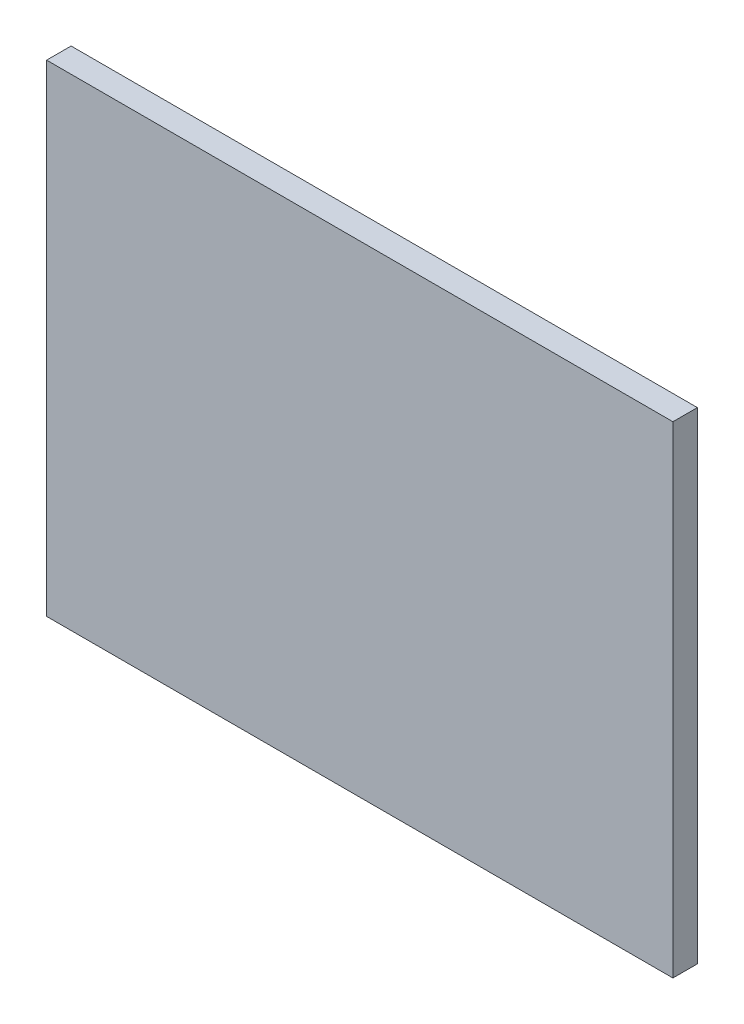
SolidWorks part; units mm, degrees
ref_plane "Front Plane" through (0, 0, 0) normal (0, 0, 1) x (1, 0, 0)
ref_plane "Top Plane" through (0, 0, 0) normal (0, 1, 0) x (1, 0, 0)
ref_plane "Right Plane" through (0, 0, 0) normal (1, 0, 0) x (0, 0, -1)
sketch "Sketch1" plane through (0, 0, 0) normal (0, 0, 1) x (1, 0, 0)
  line L1 (32.5, -25) -> (-32.5, -25)
  line L2 (32.5, -25) -> (32.5, 25)
  line L3 (32.5, 25) -> (-32.5, 25)
  line L4 (-32.5, -25) -> (-32.5, 25)
  line L5 (32.5, -25) -> (-32.5, 25) construction
  line L6 (32.5, 25) -> (-32.5, -25) construction
  point P0 (0, 0)
  dimension "D1" = 50
  dimension "D2" = 65
extrude "Boss-Extrude1" add sketch "Sketch1" along normal blind 2.54
sketch "Sketch2" plane through (0, 0, 2.54) normal (0, 0, 1) x (1, 0, 0)
  line L0 (-12.0406, -22.1111) -> (-8.0999, -14.8646)
  line L1 (-8.0999, -14.8646) -> (-11.0508, -13.6133)
  line L2 (-11.0508, -13.6133) -> (-15.6265, -19.7205)
  line L3 (-15.6265, -19.7205) -> (-12.0406, -22.1111)
  line L4 (-11.8675, -16.6471) -> (-10.4045, -17.5548)
  line L5 (-10.4045, -17.5548) -> (-9.1551, -15.3229)
  line L6 (-9.1551, -15.3229) -> (-10.6608, -15.1093)
  line L7 (-10.6608, -15.1093) -> (-11.8675, -16.6471)
  line L8 (-12.6879, -17.8424) -> (-13.7914, -19.121)
  line L9 (-13.7914, -18.1576) -> (-12.5653, -18.9809)
  line L10 (-16.1474, 2.0689) -> (-16.5784, 2.8101)
  line L11 (-16.5784, 2.8101) -> (-15.9751, 4.1202)
  line L12 (-15.9751, 4.1202) -> (-15.0615, 4.3098)
  line L13 (-15.0615, 4.3098) -> (-14.2331, 3.3179)
  line L14 (-14.2331, 3.3179) -> (-16.1474, 2.0689)
  line L15 (-14.2331, 3.3179) -> (-13.3481, 2.2583)
  line L16 (-13.3481, 2.2583) -> (-14.0719, 0.6866)
  line L17 (-14.0719, 0.6866) -> (-13.0102, 0.483)
  line L18 (-13.0102, 0.483) -> (-11.5568, 0.7846)
  line L19 (-11.5568, 0.7846) -> (-11.0508, 2.4395)
  line L20 (-11.0508, 2.4395) -> (-11.6794, 2.6317)
  line L21 (-11.6794, 2.6317) -> (-13.3481, 2.2583)
  line L22 (-11.6794, 2.6317) -> (-11.6794, 4.3098)
  line L23 (-11.6794, 4.3098) -> (-12.8281, 4.4649)
  line L24 (-12.8281, 4.4649) -> (-14.2331, 3.3179)
  line L25 (-12.8281, 4.4649) -> (-13.3481, 5.482)
  line L26 (-13.3481, 5.482) -> (-14.2331, 5.3268)
  line L27 (-14.2331, 5.3268) -> (-14.8029, 4.9821)
  line L28 (-14.8029, 4.9821) -> (-15.0615, 4.3098)
  line L29 (-11.5568, 0.7846) -> (-8.6275, 2.0689)
  line L30 (-8.6275, 2.0689) -> (-5.8634, 1.7504)
  line L31 (-14.0719, 0.6866) -> (-14.8774, 0.7794)
  line L32 (-17.9792, 2.713) -> (-18.9998, 4.1202)
  line L33 (-18.9998, 4.1202) -> (-19.9976, 3.7421)
  line L34 (-19.9976, 3.7421) -> (-20.847, 2.8481)
  line L35 (-20.847, 2.8481) -> (-21.1712, 3.2951)
  line L36 (-21.1712, 3.2951) -> (-21.0091, 4.7032)
  line L37 (-21.0091, 4.7032) -> (-19.5424, 6.2468)
  line L38 (-19.5424, 6.2468) -> (-18.4895, 5.475)
  line L39 (-18.4895, 5.475) -> (-18.9998, 4.1202)
  line L40 (-18.4895, 5.475) -> (-17.1317, 5.475)
  line L41 (-17.1317, 5.475) -> (-15.9751, 4.1202)
  line L42 (-17.1317, 5.475) -> (-17.1317, 6.2468)
  line L43 (-17.1317, 6.2468) -> (-15.0615, 6.834)
  line L44 (-15.0615, 6.834) -> (-14.4556, 5.8609)
  line L45 (-14.4556, 5.8609) -> (-14.0719, 5.3551)
  line L46 (-11.0508, 2.4395) -> (-9.8042, 3.3179)
  line L47 (-9.8042, 3.3179) -> (-8.4112, 2.8787)
  line L48 (-8.4112, 2.8787) -> (-8.6275, 2.0689)
  line L49 (-9.8042, 3.3179) -> (-9.8042, 4.1202)
  line L50 (-9.8042, 4.1202) -> (-11.6794, 4.9821)
  line L51 (-11.6794, 4.9821) -> (-11.9703, 4.3491)
  line L52 (-11.6794, 4.9821) -> (-11.8675, 5.567)
  line L53 (-11.8675, 5.567) -> (-11.6023, 6.4083)
  line L54 (-11.6023, 6.4083) -> (-10.857, 7.635)
  line L55 (-10.857, 7.635) -> (-9.7221, 7.1684)
  line L56 (-9.7221, 7.1684) -> (-9.1551, 5.567)
  line L57 (-9.1551, 5.567) -> (-10.2168, 4.3098)
  line L58 (-13.5123, 5.4532) -> (-13.3481, 6.4083)
  line L59 (-13.3481, 6.4083) -> (-12.5653, 6.834)
  line L60 (-12.5653, 6.834) -> (-11.6023, 6.4083)
  line L61 (-15.0615, 6.834) -> (-15.0615, 7.2987)
  line L62 (-15.0615, 7.2987) -> (-14.4556, 7.7382)
  line L63 (-14.4556, 7.7382) -> (-13.7356, 7.9424)
  line L64 (-13.7356, 7.9424) -> (-12.8281, 6.6911)
  line L65 (-16.9544, 6.297) -> (-17.1317, 6.922)
  line L66 (-17.1317, 6.922) -> (-17.1317, 8.1816)
  line L67 (-17.1317, 8.1816) -> (-16.5784, 8.5513)
  line L68 (-16.5784, 8.5513) -> (-15.8076, 8.2313)
  line L69 (-15.8076, 8.2313) -> (-15.3466, 8.0399)
  line L70 (-15.3466, 8.0399) -> (-15.0615, 7.2987)
  line L71 (-19.016, 5.8609) -> (-18.4895, 7.2987)
  line L72 (-18.4895, 7.2987) -> (-17.1317, 8.1816)
  line L73 (-18.4895, 7.2987) -> (-19.016, 7.4915)
  line L74 (-19.016, 7.4915) -> (-20.2516, 7.635)
  line L75 (-21.0091, 4.7032) -> (-22.5161, 5.4117)
  line L76 (-17.1317, 8.1816) -> (-17.505, 9.4976)
  line L77 (-16.5784, 8.5513) -> (-15.8076, 8.5513)
  line L78 (-15.8076, 8.5513) -> (-16.4497, 10.1095)
  line L79 (-15.8076, 8.5513) -> (-14.4556, 9.009)
  line L80 (-14.4556, 9.009) -> (-13.7356, 7.9424)
  line L81 (-14.4556, 9.009) -> (-15.3466, 10.6357)
  line L82 (-14.4556, 9.009) -> (-13.7356, 9.2013)
  line L83 (-13.7356, 9.2013) -> (-12.5653, 9.009)
  line L84 (-12.5653, 9.009) -> (-11.9703, 8.5513)
  line L85 (-11.9703, 8.5513) -> (-11.6023, 8.6496)
  line L86 (-11.6023, 8.6496) -> (-10.6608, 9.4976)
  line L87 (-10.6608, 9.4976) -> (-10.2168, 9.156)
  line L88 (-10.2168, 9.156) -> (-9.5945, 10.726)
  line L89 (-12.5653, 6.834) -> (-12.0981, 8.6496)
  line L90 (-11.6023, 8.6496) -> (-11.395, 8.0399)
  line L91 (-11.395, 8.0399) -> (-10.857, 7.635)
  line L92 (-9.7221, 7.1684) -> (-9.4383, 7.6356)
  line L93 (-9.4383, 7.6356) -> (-9.7221, 8.8809)
  line L94 (-9.7221, 8.8809) -> (-10.2168, 9.156)
  line L95 (-9.4383, 7.6356) -> (-9.0078, 7.4915)
  line L96 (-9.0078, 7.4915) -> (-8.4112, 7.5635)
  line L97 (-8.4112, 7.5635) -> (-7.3935, 7.223)
  line L98 (-7.3935, 7.223) -> (-7.0721, 7.3932)
  line L99 (-7.0721, 7.3932) -> (-7.3935, 7.7382)
  line L100 (-7.3935, 7.7382) -> (-6.7875, 9.0337)
  line L101 (-8.4112, 2.8787) -> (-7.7704, 3.636)
  line L102 (-7.7704, 3.636) -> (-7.536, 4.7032)
  line L103 (-7.536, 4.7032) -> (-8.2547, 5.4532)
  line L104 (-8.2547, 5.4532) -> (-9.1551, 5.567)
  line L105 (-7.0721, 7.3932) -> (-6.9087, 6.6911)
  line L106 (-6.9087, 6.6911) -> (-6.9087, 6.1502)
  line L107 (-6.9087, 6.1502) -> (-7.7704, 4.9478)
  line L108 (-7.7704, 4.9478) -> (-6.9904, 5.1293)
  line L109 (-6.9904, 5.1293) -> (-6.2768, 4.7874)
  line L110 (-6.2768, 4.7874) -> (-5.6374, 4.1202)
  line L111 (-5.6374, 4.1202) -> (-5.9571, 3.4529)
  line L112 (-5.9571, 3.4529) -> (-6.6336, 3.1655)
  line L113 (-6.6336, 3.1655) -> (-7.7704, 3.636)
  line L114 (-5.9571, 3.4529) -> (-5.3806, 1.6706)
  line L115 (-5.6374, 4.1202) -> (-4.276, 3.9967)
  line L116 (-4.276, 3.9967) -> (-3.3419, 2.5617)
  line L117 (-4.276, 3.9967) -> (-4.0369, 4.9478)
  line L118 (-4.0369, 4.9478) -> (-3.3419, 6.0192)
  line L119 (-6.2768, 4.7874) -> (-5.5609, 5.1293)
  line L120 (-5.5609, 5.1293) -> (-5.1826, 6.297)
  line L121 (-5.1826, 6.297) -> (-6.9087, 6.4206)
  line L122 (-5.1826, 6.297) -> (-3.771, 6.5273)
  line L123 (-5.1826, 6.297) -> (-3.9456, 5.0884)
  line L124 (-5.1826, 6.297) -> (-5.2524, 7.0411)
  line L125 (-5.2524, 7.0411) -> (-5.0386, 7.7012)
  circle A0 centre (-12.8281, -20.0931) radius 0.283
  circle A1 centre (-11.9611, -19.8829) radius 0.2943
  arc A2 (-24.1915, -9.6167) -> (-22.671, -9.6167) centre (-23.4312, -4.084) ccw
  circle A3 centre (-10.0922, -5.1616) radius 0.2974
  arc A4 (-1.0578, 5.3551) -> (0.6251, 5.4996) centre (0.0024, 2.8812) cw
  arc A5 (-1.5143, 7.0411) -> (0.6895, 7.3932) centre (-0.0583, 5.001) cw
  ellipse E0 centre (-3.3419, -13.334) end of major axis (-2.8191, -13.104) minor radius 0.2512
  spline S0 degree 3 poles (-27.5251, -13.088) (-24.0579, -14.1576) (-20.2746, -14.1555) (-16.7511, -11.9181) (-13.3401, -7.7153) (-13.7853, -2.5575) (-14.9166, 1.8411) (-19.0359, 3.2037) (-23.6603, 2.6267) (-27.2975, -1.6252) (-28.744, -5.9038) (-29.7607, -9.927) (-27.5251, -13.088) (-24.0579, -14.1576) (-20.2746, -14.1555) knots -0.207898 -0.147468 -0.093823 0 0.055188 0.122965 0.238008 0.350743 0.417311 0.485494 0.581231 0.676887 0.792102 0.852532 0.906177 1 1.055188 1.122965 1.238008 only from (-23.3767, -14.0491) to (-23.3767, -14.0491)
  spline S1 degree 3 poles (-25.7296, -4.6255) (-24.8402, -5.3847) (-23.9909, -4.9713) (-23.6886, -4.0113) (-24.5107, -3.7974) (-25.0494, -4.0524) (-25.7296, -4.6255) (-24.8402, -5.3847) (-23.9909, -4.9713) knots -0.476092 -0.336225 -0.182511 0 0.217387 0.382023 0.523908 0.663775 0.817489 1 1.217387 1.382023 1.523908 only from (-24.9047, -5.1616) to (-24.9047, -5.1616)
  spline S2 degree 3 poles (-18.6472, -3.8048) (-19.3667, -4.878) (-18.2288, -4.7529) (-17.787, -4.0416) (-18.6472, -3.8048) (-19.3667, -4.878) (-18.2288, -4.7529) knots -0.72564 -0.511435 -0.33395 0 0.27436 0.488565 0.66605 1 1.27436 1.488565 1.66605 only from (-18.9998, -4.6811) to (-18.9998, -4.6811)
  spline S3 degree 2 poles (-15.0615, -14.0491) (-15.8669, -16.1501) (-14.4556, -18.1576) knots 0 0 0 1 1 1
  spline S4 degree 2 poles (-16.5784, -14.2169) (-18.177, -15.7842) (-18.9998, -17.8424) knots 0 0 0 1 1 1
  spline S5 degree 3 poles (-21.7687, -14.1058) (-12.7126, -15.108) (-3.659, -11.6434) (4.172, -7.4906) knots 0 0 0 0 1 1 1 1
  spline S6 degree 1 poles (4.172, -7.4906) (9.3773, -3.6101) knots 0 0 1 1
  spline S7 degree 1 poles (9.3773, -3.6101) (3.0489, -4.3132) knots 0 0 1 1
  spline S8 degree 3 poles (3.7668, -7.7042) (4.5774, -6.9263) (3.629, -5.2317) (0.4265, -1.8327) (-2.3852, 1.2814) (-5.8634, 1.7504) knots 0 0 0 0 0.191567 0.332683 1 1 1 1
  spline S9 degree 3 poles (-25.7778, 0) (-24.5519, 1.9069) (-22.9237, 5.8626) (-18.3026, 9.0708) (-14.2083, 11.4673) (-9.6967, 11.201) (-5.5889, 8.1397) (-2.5037, 5.8554) (-2.2052, 3.3179) knots 0 0 0 0 0.216521 0.384343 0.520061 0.656934 0.777534 1 1 1 1
  spline S10 degree 2 poles (-5.3806, 1.6706) (-3.646, 2.2171) (-2.2052, 3.3179) knots 0 0 0 1 1 1
  spline S11 degree 3 poles (-10.6608, 1.1775) (-9.0493, -0.6272) (-9.8427, -3.2055) (-10.6608, -5.1616) knots 0 0 0 0 1 1 1 1
  spline S12 degree 3 poles (-9.4383, -5.1616) (-8.3081, -2.9675) (-8.4524, -0.4904) (-8.8717, 1.9618) knots 0 0 0 0 1 1 1 1
  spline S13 degree 3 poles (-10.6608, -5.1616) (-11.1424, -5.7321) (-9.8449, -6.135) (-9.6198, -5.5142) (-9.4383, -5.1616) knots 0 0 0 0 0.603542 1 1 1 1
  spline S14 degree 3 poles (-4.0369, -10.4218) (-5.58, -9.4393) (-2.3889, -9.7419) (-4.7119, -7.9229) (-2.6861, -7.5299) (-4.7908, -6.566) (-2.9814, -6.0165) (-3.8781, -5.3455) (-2.6162, -4.373) (-5.0202, -4.7293) (-2.2407, -3.1007) (-4.4101, -3.0229) (-2.7045, -2.0053) (-4.974, -2.4526) (-2.5786, -1.2157) (-4.7213, -1.3687) (-3.6519, -0.487) (-5.0839, -0.6913) (-4.0785, 0.3957) (-5.849, -0.1511) (-4.7666, 0) knots 0 0 0 0 0.112262 0.188112 0.238123 0.304725 0.364837 0.391002 0.445606 0.495483 0.585167 0.629275 0.677108 0.725559 0.787324 0.840269 0.868709 0.911521 0.9397 1 1 1 1
  spline S15 degree 3 poles (-5.8634, 1.1775) (-3.8348, -2.7459) (-4.2591, -7.5405) (-5.8634, -11.5212) knots 0 0 0 0 1 1 1 1
  spline S16 degree 3 poles (-6.6336, -11.4268) (-5.0632, -11.8299) (-3.516, -10.8334) (-2.0532, -10.4775) knots 0 0 0 0 1 1 1 1
  spline S17 degree 3 poles (-4.0369, 0.483) (-1.2309, -2.5764) (-1.4695, -7.1744) (-2.8191, -10.7967) knots 0 0 0 0 1 1 1 1
  spline S18 degree 3 poles (-19.7109, -13.923) (-20.6263, -14.6264) (-14.1256, -11.4385) (-16.5784, -14.2169) knots 0 0 0 0 1 1 1 1
  spline S19 degree 2 poles (-16.5784, -14.2169) (-15.0606, -13.4238) (-13.3481, -13.334) knots 0 0 0 1 1 1
  spline S20 degree 2 poles (-13.5123, -13.6133) (-11.7446, -13.1184) (-9.9669, -12.6618) knots 0 0 0 1 1 1
  spline S21 degree 3 poles (-9.8042, -12.2834) (-9.0556, -12.3875) (-8.2001, -12.4371) (-7.536, -11.9943) knots 0 0 0 0 1 1 1 1
  spline S22 degree 2 poles (-27.8331, -4.0855) (-26.9676, -2.0762) (-25.2194, -0.8587) knots 0 0 0 1 1 1
  spline S23 degree 2 poles (-26.5073, -1.7308) (-25.4526, -0.7452) (-25.2194, 0.6327) knots 0 0 0 1 1 1
  spline S24 degree 2 poles (-17.5328, 9.4805) (-17.7767, 9.9475) (-17.505, 10.3251) knots 0 0 0 1 1 1
  spline S25 degree 3 poles (-12.6879, -12.8416) (-10.8824, -9.711) (-11.8895, -5.1964) (-11.4134, -0.7134) (-11.9703, 0.2853) knots 0 0 0 0 0.75854 1 1 1 1
  spline S26 degree 2 poles (-8.8495, -12.3537) (-7.1811, -8.3584) (-9.1551, -4.542) knots 0 0 0 1 1 1
  spline S27 degree 3 poles (-10.4045, -11.9943) (-9.0302, -11.1603) (-11.3, -11.7914) (-9.7756, -10.8444) (-9.5302, -10.4884) (-8.8628, -9.9111) (-9.9482, -10.7513) (-10.6689, -9.879) (-9.6384, -9.7491) (-10.3299, -8.3784) (-9.2416, -9.4055) (-9.4719, -8.4453) (-9.4383, -8.8286) knots 0 0 0 0 0.176842 0.309705 0.384902 0.440499 0.563037 0.653214 0.734043 0.850283 0.931205 1 1 1 1
  spline S28 degree 3 poles (-9.8042, -9.1809) (-10.209, -8.7944) (-8.584, -8.0869) (-10.6604, -8.0511) (-6.5647, -5.0403) (-12.5561, -8.3877) (-10.4045, -5.8581) knots 0 0 0 0 0.181659 0.268729 0.519428 1 1 1 1
  spline S29 degree 3 poles (-11.395, -2.8802) (-9.674, -2.9282) (-11.3171, -2.077) (-10.2046, -1.5883) (-10.8643, -1.4372) (-9.4889, -0.6392) (-10.8129, 0.9765) (-11.395, -0.5707) knots 0 0 0 0 0.285359 0.365277 0.429359 0.517511 1 1 1 1
  spline S30 degree 3 poles (-2.2052, 0.7846) (-0.9984, 2.9148) (-0.3321, 6.0255) (-2.2052, 8.0399) knots 0 0 0 0 1 1 1 1
  spline S31 degree 3 poles (-1.9213, 7.7012) (-1.7075, 8.732) (0.325, 9.6826) (2.5658, 7.4865) (1.4686, 3.6369) (-0.5582, 1.7215) (-1.2167, -0.3698) knots 0 0 0 0 0.20746 0.380583 0.549219 1 1 1 1
  spline S32 degree 2 poles (0.3658, 9.0337) (1.2262, 5.8361) (0.3072, 2.5617) knots 0 0 0 1 1 1
  spline S33 degree 2 poles (-1.5622, 2.1632) (-0.7759, 2.2659) (-0.0795, 1.9618) knots 0 0 0 1 1 1
  spline S34 degree 2 poles (-1.2167, 3.3179) (0.5111, 2.9449) (0.6251, 3.9967) knots 0 0 0 1 1 1
  spline S35 degree 3 poles (-6.2768, 13.1542) (-5.6108, 14.6832) (-5.0367, 16.1912) (-2.5524, 16.6795) (-2.9088, 16.139) knots 0 0 0 0 0.829995 1 1 1 1
  spline S36 degree 3 poles (-1.158, 15.9835) (-0.4348, 16.0611) (0.934, 17.9405) (-0.5877, 18.8694) (-1.2971, 18.7484) (-2.5635, 19.5376) (-0.1205, 20.1091) (-0.476, 20.2092) knots 0 0 0 0 0.41427 0.519833 0.672245 0.747005 1 1 1 1
  spline S37 degree 3 poles (3.0489, 16.3448) (3.0652, 16.0676) (2.5727, 16.1517) (2.5372, 16.9068) (2.5032, 17.4858) (2.5508, 18.3573) (2.0116, 18.3468) (1.8172, 18.0038) (1.3588, 17.8269) (1.014, 18.185) (1.0164, 18.6836) (0.9657, 19.4707) (1.1105, 20.1112) (0.9874, 20.5392) knots 0 0 0 0 0.075617 0.151384 0.305545 0.403884 0.443899 0.510868 0.576593 0.634424 0.705857 0.800654 1 1 1 1
  spline S38 degree 3 poles (4.4392, 18.3192) (4.3888, 18.7722) (5.3114, 19.1852) (4.7748, 20.1119) (4.0948, 19.9536) (3.8574, 19.3267) (3.8192, 18.5658) (4.0036, 17.7222) (5.021, 17.0651) (5.6564, 17.947) (5.7239, 18.3192) knots 0 0 0 0 0.19099 0.27649 0.356302 0.436745 0.550019 0.693609 0.795303 1 1 1 1
  spline S39 degree 3 poles (6.3311, 21.4597) (6.6483, 21.0869) (6.4079, 20.5748) (6.471, 19.7251) (6.5638, 19.1309) (6.4379, 17.786) (6.7824, 18.2618) knots 0 0 0 0 0.338218 0.435134 0.686847 1 1 1 1
  spline S40 degree 2 poles (7.5995, 22.7493) (7.5736, 20.6765) (7.8403, 18.6294) knots 0 0 0 1 1 1
  spline S41 degree 3 poles (-0.476, 0) (0.8104, 0.5575) (3.2926, 0.3184) (5.4546, 2.9259) (5.8653, 4.6252) (6.6273, 5.4996) knots 0 0 0 0 0.457706 0.652 1 1 1 1
  spline S42 degree 3 poles (6.6273, 5.4996) (6.9186, 4.7359) (8.0304, 3.6944) (7.9679, 1.3503) (6.0473, -1.1508) (4.4278, -3.0008) (3.0489, -4.0892) knots 0 0 0 0 0.213631 0.354579 0.557677 1 1 1 1
  spline S43 degree 3 poles (-0.102, -1.34) (1.1778, -1.4342) (3.1446, -1.0769) (6.1826, 0.7354) (6.7725, 3.0549) (7.3213, 4.3098) knots 0 0 0 0 0.371122 0.580016 1 1 1 1
  spline S44 degree 2 poles (7.4573, 2.2583) (8.2236, 1.4429) (9.1971, 0.8908) knots 0 0 0 1 1 1
  spline S45 degree 2 poles (6.233, 0.8908) (6.8115, 0.3223) (7.4573, -0.1677) knots 0 0 0 1 1 1
  spline S46 degree 2 poles (4.7247, 0) (5.3747, -0.5866) (5.8304, -1.34) knots 0 0 0 1 1 1
  spline S47 degree 2 poles (2.5467, -0.6929) (3.3585, -1.3393) (3.854, -2.2492) knots 0 0 0 1 1 1
  spline S48 degree 3 poles (0.3072, -1.734) (0.2489, -4.3508) (1.5022, -6.878) (0.1302, -9.5061) knots 0 0 0 0 1 1 1 1
  spline S49 degree 2 poles (1.8599, -8.6761) (2.9357, -6.1685) (1.9927, -3.4901) knots 0 0 0 1 1 1
  spline S50 degree 3 poles (0.6251, -3.2039) (1.2828, -2.5644) (2.0799, -3.9012) (0.7546, -4.7727) (1.6088, -5.4872) (0.4666, -6.4436) (2.3825, -7.0164) (1.3621, -7.7042) knots 0 0 0 0 0.29038 0.477223 0.583713 0.711022 1 1 1 1
  spline S51 degree 3 poles (4.4392, -4.6026) (6.1142, -4.5444) (3.5075, -6.2178) (6.4865, -5.1371) (6.9338, -3.6029) (6.233, -5.1616) knots 0 0 0 0 0.335713 0.597738 1 1 1 1
  spline S52 degree 3 poles (5.3956, -5.6925) (4.9219, -7.6122) (5.451, -3.5619) (5.7809, -6.2695) (7.9166, -3.933) (5.0674, -4.9394) (3.8552, -4.7576) (4.7247, -6.1302) knots 0 0 0 0 0.261189 0.34692 0.539272 0.692266 1 1 1 1
  spline S53 degree 3 poles (12.3064, -2.2492) (14.6032, -1.4072) (16.9057, -0.3528) (19.378, -0.1677) knots 0 0 0 0 1 1 1 1
  spline S54 degree 2 poles (7.8403, -4.7559) (9.2415, -4.0879) (10.7178, -3.6101) knots 0 0 0 1 1 1
  spline S55 degree 2 poles (21.1907, 1.0008) (21.7994, -0.3621) (21.6659, -1.864) knots 0 0 0 1 1 1
  spline S56 degree 3 poles (21.6659, -2.8802) (22.2626, -3.0118) (23.9759, -2.1956) (23.2172, -1.0222) (22.0181, -0.3114) (23.1609, -0.2471) (23.5943, 0.2372) (23.5556, 0.9876) (22.7882, 1.3375) (22.1254, 1.7489) (21.9669, 1.1775) knots 0 0 0 0 0.296129 0.388383 0.521882 0.607162 0.687035 0.764916 0.850562 1 1 1 1
  spline S57 degree 3 poles (25.246, 1.1775) (25.3421, 0.4705) (25.1085, -0.4497) (24.9812, -1.619) (25.5132, -2.3995) (26.5375, -1.9825) (27.5582, -1.8866) (27.3183, -1.34) knots 0 0 0 0 0.352422 0.503149 0.587133 0.784575 1 1 1 1
  spline S58 degree 2 poles (25.2151, 0) (26.1789, 0.2335) (27.1738, 0.1949) knots 0 0 0 1 1 1
  spline S59 degree 2 poles (25.6262, 1.515) (26.5926, 2.1782) (27.7499, 1.4224) knots 0 0 0 1 1 1
  spline S60 degree 3 poles (28.4563, 1.1775) (28.7743, 0.1765) (27.9329, -0.8212) (28.4587, -2.2267) (29.338, -2.0162) (30.2045, -1.7432) (31.1802, -1.1386) (30.1968, -0.6929) knots 0 0 0 0 0.446063 0.50553 0.612742 0.774479 1 1 1 1
  spline S61 degree 3 poles (28.5636, 0.1949) (28.6887, 0.7279) (30.8098, 0.2484) (30.1968, 1.0008) knots 0 0 0 0 1 1 1 1
  spline S62 degree 2 poles (29.019, 1.7504) (30.0707, 2.1477) (31.1901, 2.2583) knots 0 0 0 1 1 1
  spline S63 degree 2 poles (-5.8634, -17.8424) (-1.0442, -17.8286) (3.7668, -17.5548) knots 0 0 0 1 1 1
  spline S64 degree 2 poles (6.8944, -15.3229) (7.8311, -20.0367) (6.9609, -18.1576) knots 0 0 0 1 1 1
  spline S65 degree 3 poles (5.0867, -14.7857) (6.5132, -14.5414) (7.4754, -14.0906) (9.233, -13.7362) (9.1068, -14.5987) knots 0 0 0 0 0.26483 1 1 1 1
  spline S66 degree 3 poles (9.6928, -18.041) (9.8546, -17.7729) (10.1511, -17.2815) (11.0399, -16.4796) (9.99, -15.9906) (9.3903, -16.6748) (9.2809, -17.5057) (9.6636, -18.2085) (10.4459, -18.8391) (10.8424, -18.3084) (11.0422, -18.041) knots 0 0 0 0 0.154179 0.282628 0.391103 0.503634 0.642468 0.745561 0.871779 1 1 1 1
  spline S67 degree 3 poles (13.243, -16.0323) (12.719, -15.83) (11.7843, -16.6378) (12.2849, -17.5131) (12.8384, -18.5124) (13.7982, -17.3806) (13.7843, -17.0721) knots 0 0 0 0 0.356569 0.516563 0.659491 1 1 1 1
  spline S68 degree 3 poles (14.4395, -15.5623) (14.39, -16.2692) (14.6018, -16.8256) (14.3633, -18.0847) (14.992, -18.0748) (15.066, -17.5155) (15.4746, -16.8987) (16.1006, -17.3384) (16.3459, -17.8541) (16.6823, -18.3342) (16.9464, -18.041) knots 0 0 0 0 0.317273 0.422454 0.470887 0.565481 0.675082 0.768244 0.873173 1 1 1 1
  point P488 (6.9609, -18.1576)
